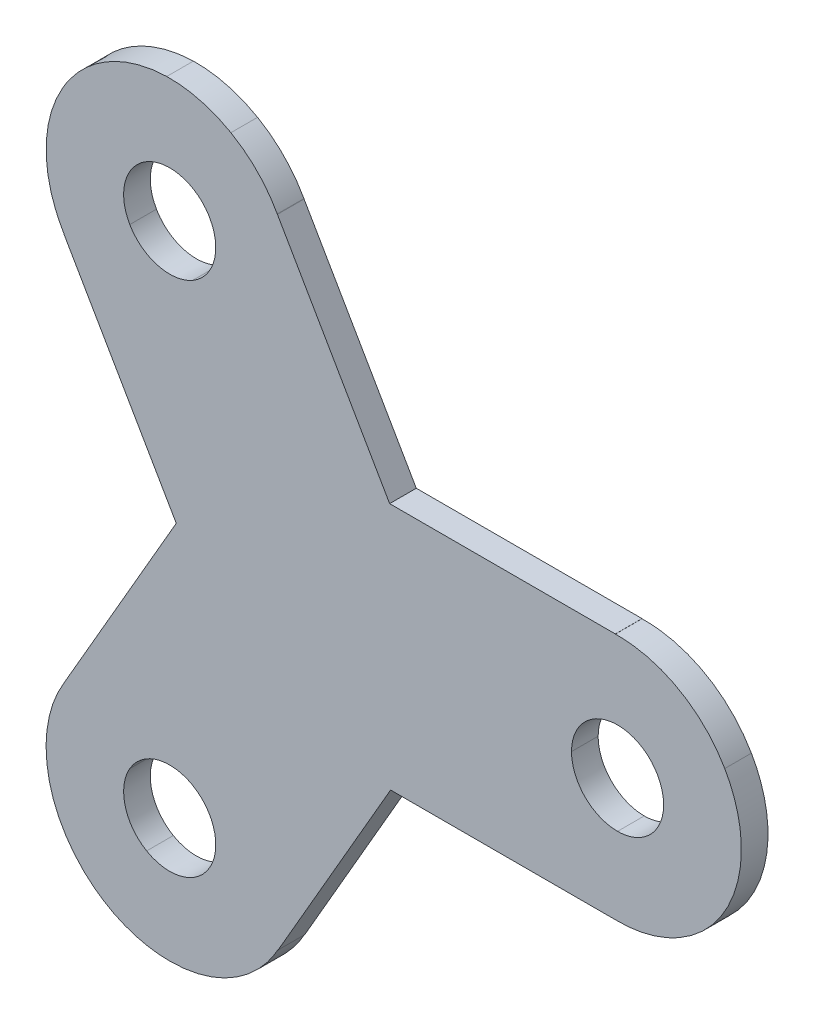
SolidWorks part; units mm, degrees
ref_plane "Front Plane" through (0, 0, 0) normal (0, 0, 1) x (1, 0, 0)
ref_plane "Top Plane" through (0, 0, 0) normal (0, 1, 0) x (1, 0, 0)
ref_plane "Right Plane" through (0, 0, 0) normal (1, 0, 0) x (0, 0, -1)
sketch "carrier" plane through (-89.6124, 67.4585, 0) normal (0, 0, 1) x (1, 0, 0)
  line L796 (118.819, 161.9893) -> (118.8102, 161.9805)
  line L797 (118.8102, 161.9805) -> (125.513, 150.383)
  line L798 (125.513, 150.383) -> (118.819, 138.7942)
  line L799 (118.819, 138.7942) -> (118.8102, 138.7766)
  line L801 (131.5719, 131.4123) -> (131.5807, 131.4035)
  line L802 (131.5807, 131.4035) -> (138.2835, 143.0099)
  line L803 (138.2835, 143.0099) -> (151.6538, 143.0099)
  line L804 (151.6538, 143.0099) -> (151.6714, 143.0099)
  line L806 (151.6714, 157.7472) -> (151.6714, 157.7548)
  line L807 (151.6714, 157.7548) -> (138.225, 157.7548)
  line L808 (138.225, 157.7548) -> (131.5398, 169.3348)
  line L809 (131.5398, 169.3348) -> (131.531, 169.3524)
  line L811 (131.3482, 148.2249) -> (136.684, 148.2249)
  line L813 (136.684, 152.5376) -> (131.3482, 152.5376)
  spline S1 degree 3 poles (124.9469, 173.1541) (122.467, 173.0886) (120.0788, 171.7725) (118.7485, 169.4682) knots 0.003756 0.003756 0.003756 0.003756 1 1 1 1
  spline S8 degree 3 poles (154.5471, 150.3813) (154.5471, 148.866) (153.3187, 147.6376) (151.8034, 147.6376) knots 0 0 0 0 1 1 1 1
  spline S9 degree 3 poles (151.8034, 147.6376) (150.2881, 147.6376) (149.0597, 148.866) (149.0597, 150.3813) knots 0 0 0 0 1 1 1 1
  spline S10 degree 3 poles (149.0597, 150.3813) (149.0597, 151.8966) (150.2881, 153.125) (151.8034, 153.125) knots 0 0 0 0 1 1 1 1
  spline S11 degree 3 poles (151.8034, 153.125) (153.3187, 153.125) (154.5471, 151.8966) (154.5471, 150.3813) knots 0 0 0 0 1 1 1 1
  spline S12 degree 3 poles (123.7501, 168.1621) (125.0624, 168.9197) (126.7404, 168.4701) (127.4981, 167.1578) knots 0 0 0 0 1 1 1 1
  spline S13 degree 3 poles (127.4981, 167.1578) (128.2557, 165.8455) (127.8061, 164.1675) (126.4938, 163.4099) knots 0 0 0 0 1 1 1 1
  spline S14 degree 3 poles (126.4938, 163.4099) (125.1815, 162.6522) (123.5035, 163.1018) (122.7459, 164.4141) knots 0 0 0 0 1 1 1 1
  spline S15 degree 3 poles (122.7459, 164.4141) (121.9882, 165.7264) (122.4378, 167.4044) (123.7501, 168.1621) knots 0 0 0 0 1 1 1 1
  spline S16 degree 3 poles (123.7501, 132.6005) (122.4378, 133.3581) (121.9882, 135.0361) (122.7459, 136.3484) knots 0 0 0 0 1 1 1 1
  spline S17 degree 3 poles (122.7459, 136.3484) (123.5035, 137.6607) (125.1815, 138.1103) (126.4938, 137.3527) knots 0 0 0 0 1 1 1 1
  spline S18 degree 3 poles (126.4938, 137.3527) (127.8061, 136.595) (128.2557, 134.917) (127.4981, 133.6047) knots 0 0 0 0 1 1 1 1
  spline S19 degree 3 poles (127.4981, 133.6047) (126.7404, 132.2924) (125.0624, 131.8428) (123.7501, 132.6005) knots 0 0 0 0 1 1 1 1
  spline S21 degree 3 poles (118.7485, 169.4682) (117.3603, 167.0639) (117.4832, 164.2113) (118.819, 161.9893) knots 0 0 0 0 1 1 1 1
  spline S22 degree 3 poles (118.8102, 138.7766) (118.1389, 137.6657) (117.7607, 136.368) (117.7607, 134.9754) knots 0 0 0 0 1 1 1 1
  spline S23 degree 3 poles (117.7607, 134.9754) (117.7607, 130.9057) (121.064, 127.6023) (125.1337, 127.6023) knots 0 0 0 0 1 1 1 1
  spline S24 degree 3 poles (125.1337, 127.6023) (127.91, 127.6023) (130.3156, 129.1445) (131.5719, 131.4123) knots 0 0 0 0 1 1 1 1
  spline S25 degree 3 poles (151.6714, 143.0099) (152.9691, 142.984) (154.2842, 143.3014) (155.4902, 143.9977) knots 0 0 0 0 1 1 1 1
  spline S26 degree 3 poles (155.4902, 143.9977) (159.0147, 146.0325) (160.2239, 150.545) (158.189, 154.0695) knots 0 0 0 0 1 1 1 1
  spline S27 degree 3 poles (158.189, 154.0695) (156.8009, 156.4738) (154.2636, 157.7931) (151.6714, 157.7472) knots 0 0 0 0 1 1 1 1
  spline S28 degree 3 poles (131.531, 169.3524) (130.9047, 170.4892) (129.9766, 171.4695) (128.7705, 172.1658) knots 0 0 0 0 1 1 1 1
  spline S29 degree 3 poles (128.7705, 172.1658) (127.5657, 172.8614) (126.2442, 173.1795) (124.9469, 173.1541) knots 0 0 0 0 0.994464 0.994464 0.994464 0.994464
  spline S30 degree 3 poles (131.3482, 152.5376) (130.8705, 151.9478) (130.5809, 151.2038) (130.5809, 150.3857) knots 0 0 0 0 1 1 1 1
  spline S31 degree 3 poles (130.5809, 150.3857) (130.5809, 149.5675) (130.8705, 148.8148) (131.3482, 148.2249) knots 0 0 0 0 1 1 1 1
  spline S32 degree 3 poles (136.684, 148.2249) (137.1616, 148.8148) (137.4513, 149.5675) (137.4513, 150.3857) knots 0 0 0 0 1 1 1 1
  spline S33 degree 3 poles (137.4513, 150.3857) (137.4513, 151.2038) (137.1616, 151.9478) (136.684, 152.5376) knots 0 0 0 0 1 1 1 1
extrude "Boss-Extrude5" add sketch "carrier" along normal blind 1.5875 separate body contours S15 S14 S13 S12 | S11 S10 S9 S8 | S19 S18 S17 S16 | L797 L798 L799 S22 S23 S24 L801 L802 L803 L804 S25 S26 S27 L806 L807 L808 L809 S28 S29 S1 S21 L796
